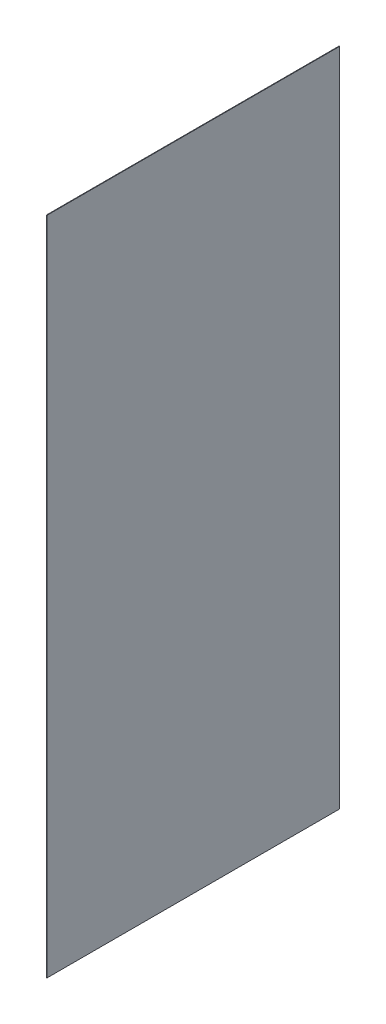
SolidWorks part; units mm, degrees
ref_plane "Front Plane" through (0, 0, 0) normal (0, 0, 1) x (1, 0, 0)
ref_plane "Top Plane" through (0, 0, 0) normal (0, 1, 0) x (1, 0, 0)
ref_plane "Right Plane" through (0, 0, 0) normal (1, 0, 0) x (0, 0, -1)
other "Configuration Table"
sketch "Sketch1" plane through (0, 0, 0) normal (0, 0, 1) x (1, 0, 0)
  line L1 (0, 120) -> (1.5, 120)
  line L2 (0, 120) -> (0, 1970)
  line L3 (0, 1970) -> (1.5, 1970)
  line L4 (1.5, 120) -> (1.5, 1970)
extrude "PACK_dis_yan_sol_1" add sketch "Sketch1" against normal blind 820 separate body
